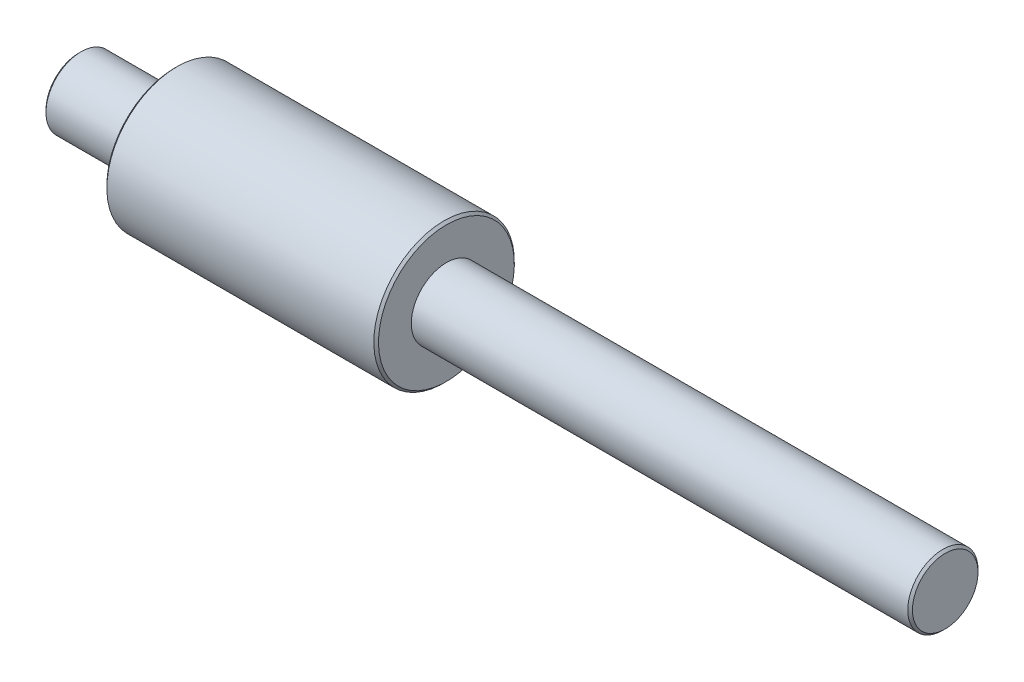
SolidWorks part; units mm, degrees
material "1.0402 (C22)"
ref_plane "Front Plane" through (0, 0, 0) normal (0, 0, 1) x (1, 0, 0)
ref_plane "Top Plane" through (0, 0, 0) normal (0, 1, 0) x (1, 0, 0)
ref_plane "Right Plane" through (0, 0, 0) normal (1, 0, 0) x (0, 0, -1)
sketch "Sketch1" plane through (0, 0, 0) normal (0, 0, 1) x (1, 0, 0)
  line L1 (-10.65, 1.5) -> (0.95, 1.5)
  line L2 (-10.65, 1.5) -> (-10.65, 0)
  line L3 (-10.65, -1.5) -> (0.95, -1.5)
  line L4 (0.95, 1.5) -> (0.95, 0)
  line L7 (0.95, -1.5) -> (22.25, -1.5)
  line L9 (0.95, 0) -> (22.25, 0)
  line L10 (22.25, -1.5) -> (22.25, 0)
  line L11 (-10.65, -1.5) -> (-14.75, -1.5)
  line L13 (-10.65, 0) -> (-14.75, 0)
  line L14 (-14.75, -1.5) -> (-14.75, 0)
  dimension "D1" = 3
  dimension "D2" = 1.5
  dimension "D3" = 1.5
  dimension "D4" = 4.1
  dimension "D5" = 21.3
  dimension "D6" = 11.6
  dimension "D7" = 21.3
  dimension "D8" = 11.6
  dimension "D9" = 4.1
revolve "Revolve2" add sketch "Sketch1" angle 360 about L11
chamfer "Chamfer3" distance 0.1 angle 45 1 edges at (-14.75, 0, 0)
chamfer "Chamfer4" distance 0.1 angle 45 1 edges at (-10.65, 1.5, 0)
chamfer "Chamfer5" distance 0.1 angle 45 1 edges at (0.95, 1.5, 0)
chamfer "Chamfer6" distance 0.1 angle 45 1 edges at (22.25, 0, 0)
